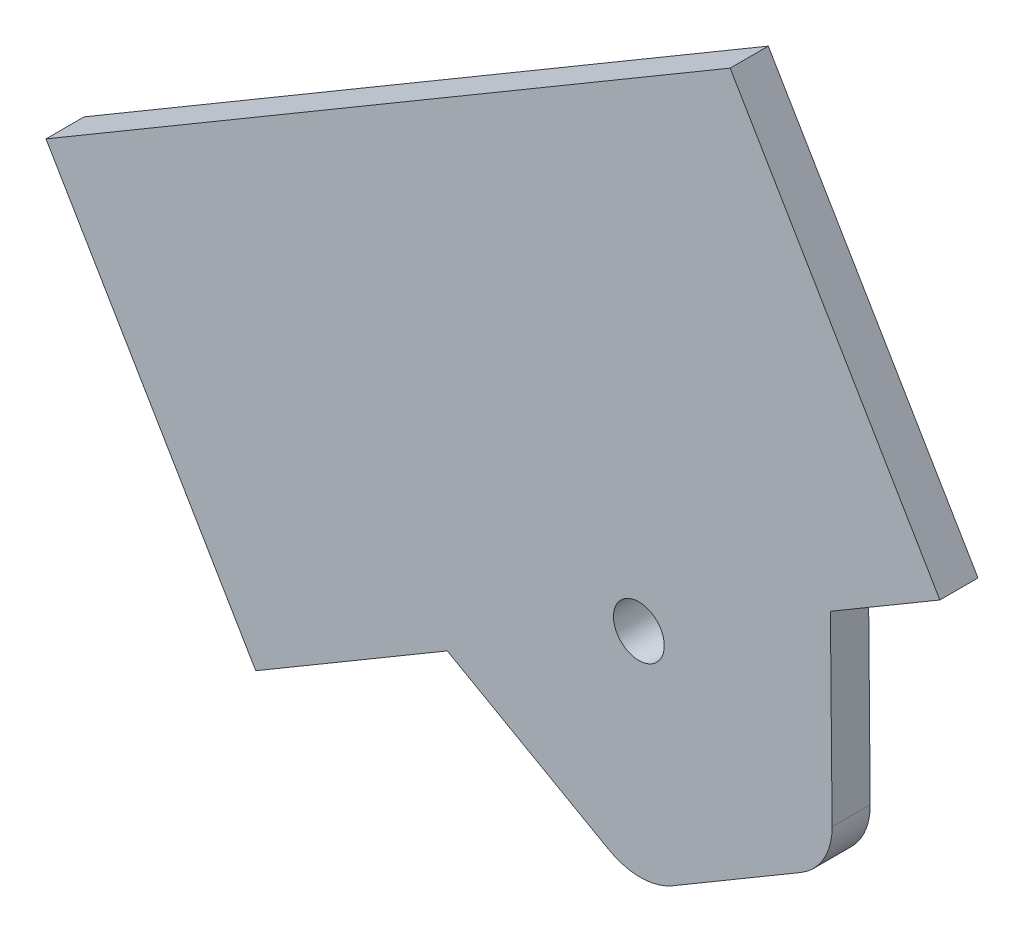
SolidWorks part; units mm, degrees
ref_plane "Front Plane" through (0, 0, 0) normal (0, 0, 1) x (1, 0, 0)
ref_plane "Top Plane" through (0, 0, 0) normal (0, 1, 0) x (1, 0, 0)
ref_plane "Right Plane" through (0, 0, 0) normal (1, 0, 0) x (0, 0, -1)
sketch "Sketch1" plane through (0, 0, 0) normal (0, 0, 1) x (1, 0, 0)
  line L7 (62.6758, 442.0969) -> (95.687, 386.1036)
  line L8 (95.687, 386.1036) -> (78.4583, 375.9463)
  line L9 (78.7244, 346.721) -> (78.4583, 375.9463)
  line L10 (53.6002, 326.1046) -> (73.8035, 338.0155)
  line L11 (18.1578, 340.3957) -> (43.6007, 326.0135)
  line L12 (-11.9925, 322.6204) -> (18.1578, 340.3957)
  line L13 (-45.0038, 378.6138) -> (-11.9925, 322.6204)
  line L15 (62.6758, 442.0969) -> (-45.0038, 378.6138)
  circle A3 centre (48.308, 358.171) radius 4
  arc A4 (73.8035, 338.0155) -> (78.7244, 346.721) centre (68.7249, 346.6299) ccw
  arc A5 (43.6007, 326.0135) -> (53.6002, 326.1046) centre (48.5216, 334.719) ccw
  dimension "D7" = 8
  dimension "D21" = 10
  dimension "D1" = 322.6204
  dimension "D2" = 11.9925
  dimension "D3" = 35
  dimension "D4" = 20
  dimension "D5" = 65
  dimension "D6" = 125
  dimension "D8" = 23.453
  dimension "D9" = 29.2253
  dimension "D10" = 35
  dimension "D11" = 90
  dimension "D12" = 90
  dimension "D13" = 90
  dimension "D14" = 90
  dimension "D15" = 120
  dimension "D16" = 60
  dimension "D17" = 60
  dimension "D18" = 35
  dimension "D19" = 284.0076
  dimension "D20" = 120
extrude "Boss-Extrude1" add sketch "Sketch1" along normal blind 6 separate body
